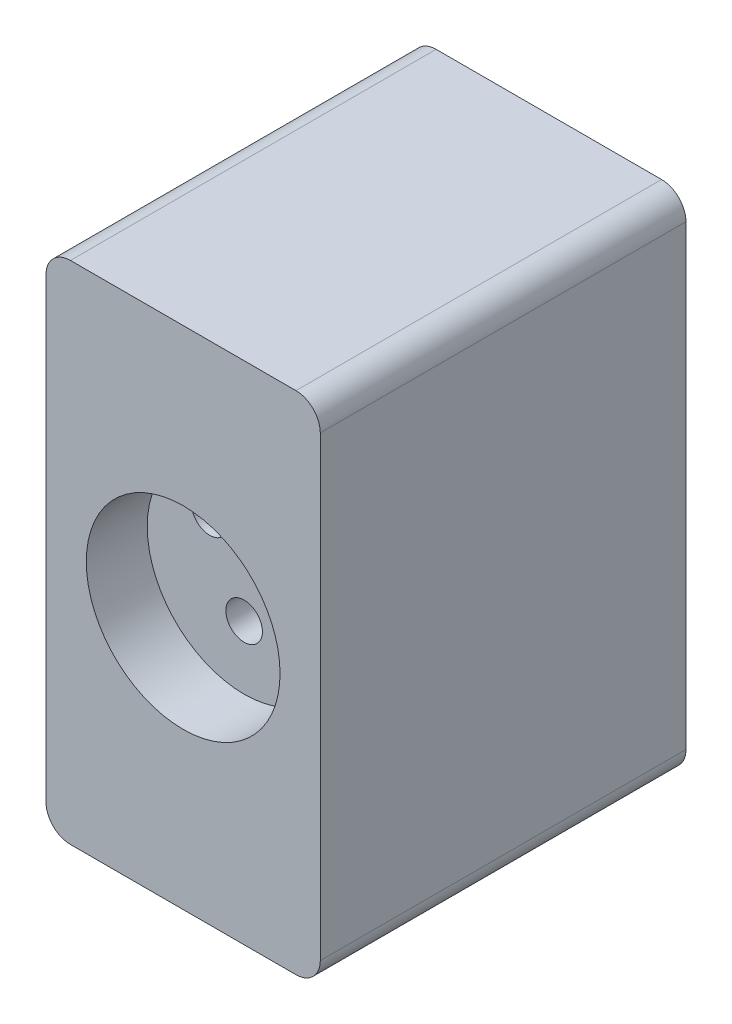
SolidWorks part; units mm, degrees
ref_plane "Front Plane" through (0, 0, 0) normal (0, 0, 1) x (1, 0, 0)
ref_plane "Top Plane" through (0, 0, 0) normal (0, 1, 0) x (1, 0, 0)
ref_plane "Right Plane" through (0, 0, 0) normal (1, 0, 0) x (0, 0, -1)
sketch "Sketch2" plane through (0, 0, 0) normal (0, 0, 1) x (1, 0, 0)
  line L1 (-18.5, -41.5) -> (18.5, -41.5)
  line L2 (-22.5, -37.5) -> (-22.5, 37.5)
  line L3 (-18.5, 41.5) -> (18.5, 41.5)
  line L4 (22.5, -37.5) -> (22.5, 37.5)
  line L5 (-22.5, -41.5) -> (22.5, 41.5) construction
  line L6 (-22.5, 41.5) -> (22.5, -41.5) construction
  arc A0 (-18.5, -41.5) -> (-22.5, -37.5) centre (-18.5, -37.5) cw
  arc A1 (18.5, -41.5) -> (22.5, -37.5) centre (18.5, -37.5) ccw
  arc A2 (22.5, 37.5) -> (18.5, 41.5) centre (18.5, 37.5) ccw
  arc A3 (-22.5, 37.5) -> (-18.5, 41.5) centre (-18.5, 37.5) cw
  point P0 (0, 0)
  dimension "D3" = 4
  dimension "D1" = 45
  dimension "D2" = 83
extrude "Boss-Extrude1" add sketch "Sketch2" along normal blind 60
sketch "Sketch3" plane through (0, 0, 60) normal (0, 0, 1) x (1, 0, 0)
  circle A0 centre (0, 0) radius 15.8958
extrude "Cut-Extrude1" cut sketch "Sketch3" against normal blind 10
sketch "Sketch4" plane through (0, 0, 50) normal (0, 0, 1) x (1, 0, 0)
  circle A0 centre (7.3388, 6.8646) radius 3
  circle A1 centre (-5.6441, 6.8646) radius 3
  circle A2 centre (0, -5.5104) radius 3
  dimension "D1" = 6
  dimension "D2" = 6
  dimension "D3" = 6
extrude "Cut-Extrude2" cut sketch "Sketch4" against normal blind 40
